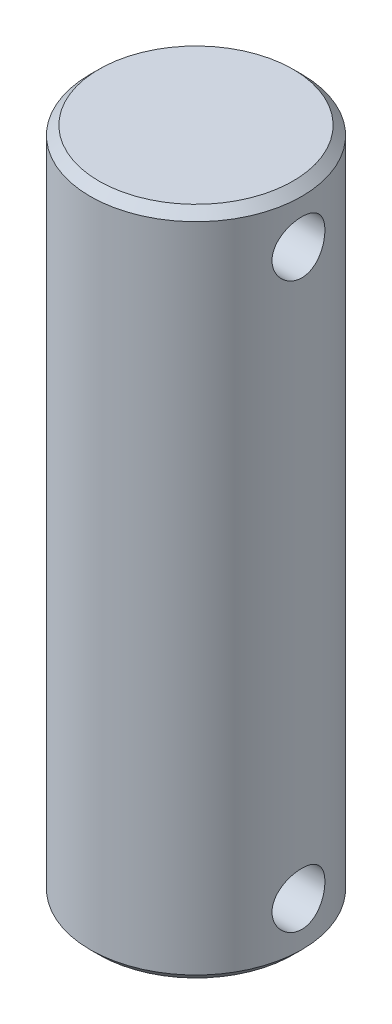
SolidWorks part; units mm, degrees
material "AISI 4340 Steel, annealed"
ref_plane "Front Plane" through (0, 0, 0) normal (0, 0, 1) x (1, 0, 0)
ref_plane "Top Plane" through (0, 0, 0) normal (0, 1, 0) x (1, 0, 0)
ref_plane "Right Plane" through (0, 0, 0) normal (1, 0, 0) x (0, 0, -1)
sketch "Sketch1" plane through (0, 0, 0) normal (0, 1, 0) x (1, 0, 0)
  circle A0 centre (0, 0) radius 6
  dimension "D1" = 12
extrude "Boss-Extrude1" add sketch "Sketch1" along normal blind 38
sketch "Sketch2" plane through (0, 0, 0) normal (1, 0, 0) x (0, 0, -1)
  line L0 (6, 38) -> (-6, 38) construction
  line L1 (-6, 0) -> (6, 0) construction
  circle A0 centre (0, 3) radius 1.5
  circle A1 centre (0, 35) radius 1.5
  dimension "D3" = 3
  dimension "D4" = 3
  dimension "D1" = 3
  dimension "D2" = 3
extrude "Cut-Extrude1" cut sketch "Sketch2" against normal through all both and the other way through all
chamfer "Chamfer1" distance 0.5 angle 45 2 edges at (0, 0, 6) (0, 38, 6)
